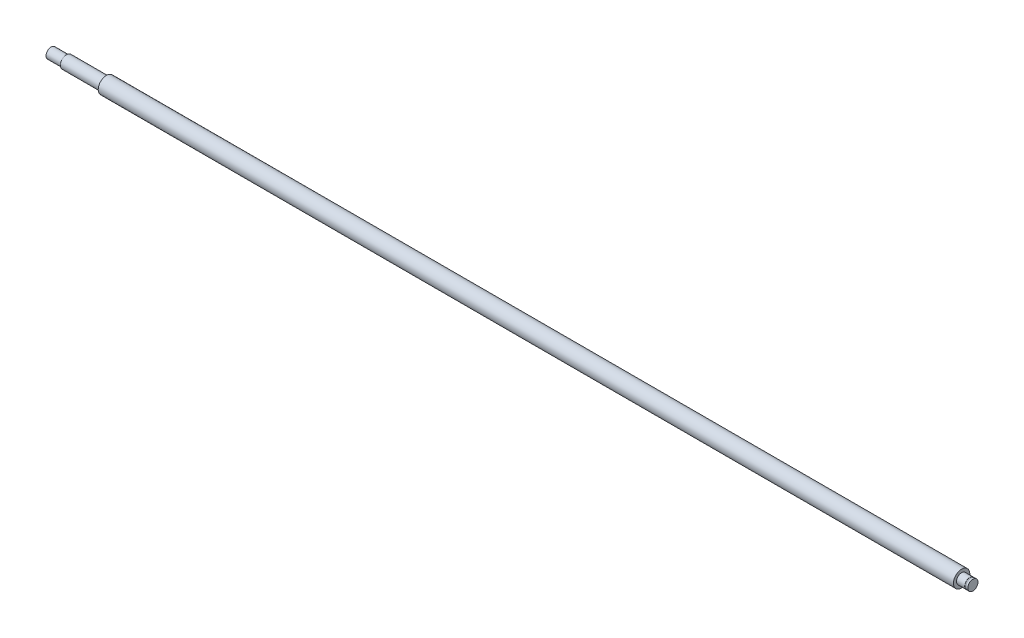
SolidWorks part; units mm, degrees
ref_plane "Front Plane" through (0, 0, 0) normal (0, 0, 1) x (1, 0, 0)
ref_plane "Top Plane" through (0, 0, 0) normal (0, 1, 0) x (1, 0, 0)
ref_plane "Right Plane" through (0, 0, 0) normal (1, 0, 0) x (0, 0, -1)
sketch "Sketch2" plane through (0, 0, 0) normal (0, 0, 1) x (1, 0, 0)
  line L0 (0, 0) -> (1582.7119, 0) construction
  line L1 (0, 0) -> (0, 5)
  line L2 (0, 5) -> (15, 5)
  line L3 (15, 5) -> (15, 6)
  line L4 (15, 6) -> (54, 6)
  line L5 (54, 6) -> (54, 8)
  line L6 (54, 8) -> (889, 8)
  line L7 (889, 8) -> (889, 5)
  line L8 (889, 5) -> (897, 5)
  line L9 (897, 5) -> (897, 4.8)
  line L10 (897, 4.8) -> (898.15, 4.8)
  line L11 (898.15, 4.8) -> (898.15, 5)
  line L12 (898.15, 5) -> (900, 5)
  line L13 (900, 5) -> (900, 0)
  line L14 (0, 0) -> (900, 0)
  dimension "D1" = 10
  dimension "D2" = 12
  dimension "D3" = 16
  dimension "D4" = 15
  dimension "D5" = 54
  dimension "D6" = 5
  dimension "D7" = 4.8
  dimension "D8" = 9.15
  dimension "D9" = 8
  dimension "D10" = 11
revolve "Revolve1" add sketch "Sketch2" angle 360 about L0
equation "\"lenght\"= 900"
equation "\"D11@Sketch2\"= \"lenght\""
equation "\"diam\"= 16"
equation "\"end_diam\"= 10"
equation "\"inner_diam\"= 12"
equation "\"D1@Sketch2\"= \"end_diam\""
equation "\"D2@Sketch2\"= \"inner_diam\""
equation "\"D6@Sketch2\"=\"end_diam\" / 2"
